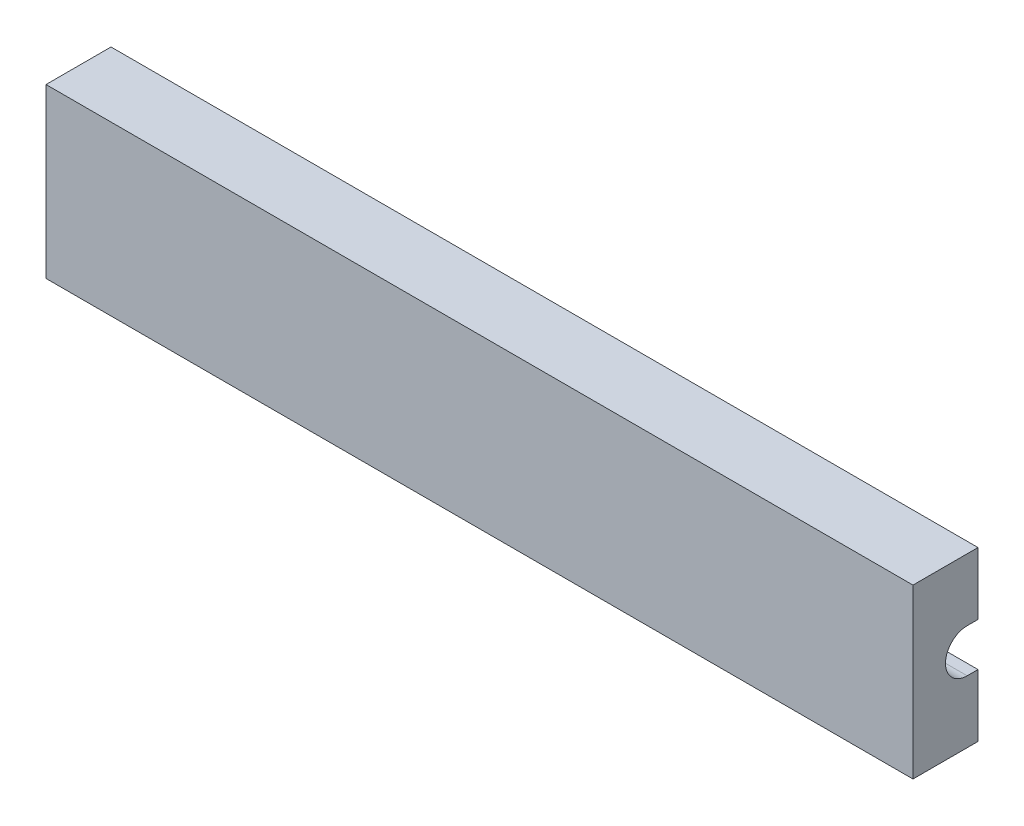
SolidWorks part; units mm, degrees
ref_plane "Front Plane" through (0, 0, 0) normal (0, 0, 1) x (1, 0, 0)
ref_plane "Top Plane" through (0, 0, 0) normal (0, 1, 0) x (1, 0, 0)
ref_plane "Right Plane" through (0, 0, 0) normal (1, 0, 0) x (0, 0, -1)
ref_plane "Plane1" through (190.6451, 0, 0) normal (1, 0, 0) x (0, 0, -1)
sketch "Sketch1" plane through (190.6451, 0, 0) normal (1, 0, 0) x (0, 0, -1)
  line L0 (-246.9709, 189.1635) -> (-240.9709, 189.1635)
  line L1 (-240.9709, 189.1635) -> (-240.9709, 183.4135)
  line L2 (-241.9709, 181.4135) -> (-240.9709, 181.4135)
  line L3 (-241.9709, 181.4135) -> (-241.9709, 183.4135)
  line L4 (-241.9709, 181.4135) -> (-241.9709, 179.4135)
  line L5 (-241.9709, 183.4135) -> (-240.9709, 183.4135)
  line L6 (-241.9709, 179.4135) -> (-240.9709, 179.4135)
  line L7 (-240.9709, 208.1635) -> (-246.9709, 208.1635)
  line L8 (-246.9709, 208.1635) -> (-246.9709, 194.1635)
  line L9 (-246.9709, 194.1635) -> (-240.9709, 194.1635)
  line L10 (-240.9709, 194.1635) -> (-240.9709, 199.9135)
  line L11 (-240.9709, 199.9135) -> (-241.5709, 199.9135)
  line L12 (-241.5709, 202.4135) -> (-240.9709, 202.4135)
  line L13 (-240.9709, 202.4135) -> (-240.9709, 208.1635)
  line L14 (-240.9709, 208.1635) -> (-246.9709, 208.1635)
  line L15 (-246.9709, 208.1635) -> (-246.9709, 194.1635)
  line L16 (-246.9709, 194.1635) -> (-240.9709, 194.1635)
  line L17 (-240.9709, 194.1635) -> (-240.9709, 199.9135)
  line L18 (-240.9709, 199.9135) -> (-241.5709, 199.9135)
  line L19 (-241.5709, 202.4135) -> (-240.9709, 202.4135)
  line L20 (-240.9709, 202.4135) -> (-240.9709, 208.1635)
  line L21 (-240.9709, 179.4135) -> (-240.9709, 173.6635)
  line L22 (-240.9709, 173.6635) -> (-246.9709, 173.6635)
  line L23 (-246.9709, 173.6635) -> (-246.9709, 189.1635)
  circle A0 centre (-241.9709, 181.4135) radius 2
  arc A1 (-241.5709, 202.4135) -> (-241.5709, 199.9135) centre (-241.5709, 201.1635) ccw
  arc A2 (-241.5709, 202.4135) -> (-241.5709, 199.9135) centre (-241.5709, 201.1635) ccw
  dimension "D3" = 1
  dimension "D4" = 4
  dimension "D1" = 0
  dimension "D2" = 5
extrude "Boss-Extrude1" add sketch "Sketch1" along normal up to vertex (60 mm away) and the other way up to vertex (20 mm away) contours A0 L5 L1 L0 L23 L22 L21 L6
